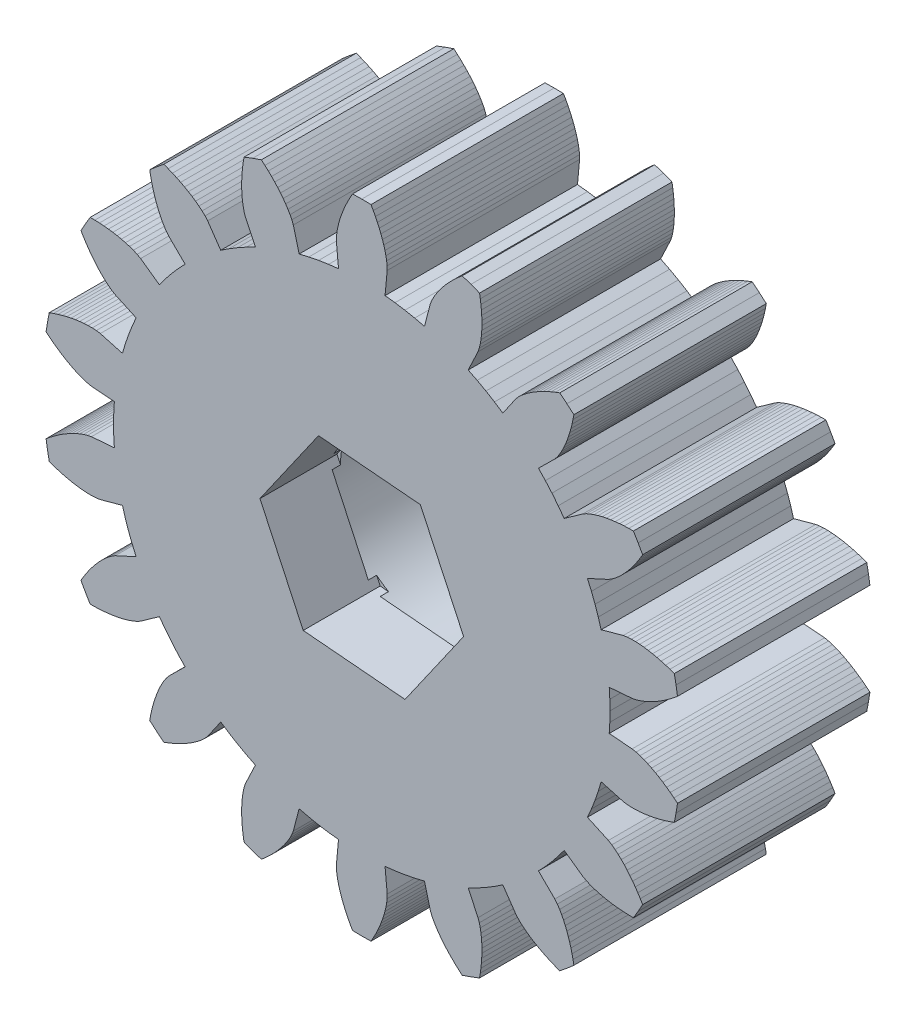
SolidWorks part; units mm, degrees
ref_plane "前视基准面" through (0, 0, 0) normal (0, 0, 1) x (1, 0, 0)
ref_plane "上视基准面" through (0, 0, 0) normal (0, 1, 0) x (1, 0, 0)
ref_plane "右视基准面" through (0, 0, 0) normal (1, 0, 0) x (0, 0, -1)
other "Configuration Table"
sketch "M1 Z18 pinion profile profile" plane through (0, 0, 0) normal (0, 0, 1) x (1, 0, 0)
  line L0 (1.344, 7.6224) -> (1.0355, 7.6704)
  line L1 (1.0355, 7.6704) -> (0.7252, 7.7059)
  line L2 (0.7252, 7.7059) -> (0.7924, 8.42)
  line L3 (0.7924, 8.42) -> (0.7898, 8.5452)
  line L4 (0.7898, 8.5452) -> (0.775, 8.6715)
  line L5 (0.775, 8.6715) -> (0.752, 8.7983)
  line L6 (0.752, 8.7983) -> (0.7221, 8.9257)
  line L7 (0.7221, 8.9257) -> (0.686, 9.0533)
  line L8 (0.686, 9.0533) -> (0.6441, 9.181)
  line L9 (0.6441, 9.181) -> (0.5969, 9.3089)
  line L10 (0.5969, 9.3089) -> (0.5446, 9.4367)
  line L11 (0.5446, 9.4367) -> (0.4873, 9.5644)
  line L12 (0.4873, 9.5644) -> (0.4253, 9.6919)
  line L13 (0.4253, 9.6919) -> (0.3586, 9.8191)
  line L14 (0.3586, 9.8191) -> (0.2874, 9.9458)
  line L15 (0.2874, 9.9458) -> (0, 9.95)
  line L16 (0, 9.95) -> (-0.2874, 9.9458)
  line L17 (-0.2874, 9.9458) -> (-0.3586, 9.8191)
  line L18 (-0.3586, 9.8191) -> (-0.4253, 9.6919)
  line L19 (-0.4253, 9.6919) -> (-0.4873, 9.5644)
  line L20 (-0.4873, 9.5644) -> (-0.5446, 9.4367)
  line L21 (-0.5446, 9.4367) -> (-0.5969, 9.3089)
  line L22 (-0.5969, 9.3089) -> (-0.6441, 9.181)
  line L23 (-0.6441, 9.181) -> (-0.686, 9.0533)
  line L24 (-0.686, 9.0533) -> (-0.7221, 8.9257)
  line L25 (-0.7221, 8.9257) -> (-0.752, 8.7983)
  line L26 (-0.752, 8.7983) -> (-0.775, 8.6715)
  line L27 (-0.775, 8.6715) -> (-0.7898, 8.5452)
  line L28 (-0.7898, 8.5452) -> (-0.7924, 8.42)
  line L29 (-0.7924, 8.42) -> (-0.7252, 7.7059)
  line L30 (-0.7252, 7.7059) -> (-1.0355, 7.6704)
  line L31 (-1.0355, 7.6704) -> (-1.344, 7.6224)
  line L32 (-1.344, 7.6224) -> (-1.6504, 7.562)
  line L33 (-1.6504, 7.562) -> (-1.9541, 7.4893)
  line L34 (-1.9541, 7.4893) -> (-2.1352, 8.1833)
  line L35 (-2.1352, 8.1833) -> (-2.1804, 8.3)
  line L36 (-2.1804, 8.3) -> (-2.2375, 8.4136)
  line L37 (-2.2375, 8.4136) -> (-2.3025, 8.5249)
  line L38 (-2.3025, 8.5249) -> (-2.3742, 8.6343)
  line L39 (-2.3742, 8.6343) -> (-2.4518, 8.7419)
  line L40 (-2.4518, 8.7419) -> (-2.5348, 8.8477)
  line L41 (-2.5348, 8.8477) -> (-2.6229, 8.9517)
  line L42 (-2.6229, 8.9517) -> (-2.7158, 9.0539)
  line L43 (-2.7158, 9.0539) -> (-2.8133, 9.1543)
  line L44 (-2.8133, 9.1543) -> (-2.9152, 9.2528)
  line L45 (-2.9152, 9.2528) -> (-3.0213, 9.3495)
  line L46 (-3.0213, 9.3495) -> (-3.1316, 9.4443)
  line L47 (-3.1316, 9.4443) -> (-3.4031, 9.3499)
  line L48 (-3.4031, 9.3499) -> (-3.6717, 9.2478)
  line L49 (-3.6717, 9.2478) -> (-3.6953, 9.1042)
  line L50 (-3.6953, 9.1042) -> (-3.7145, 8.9619)
  line L51 (-3.7145, 8.9619) -> (-3.7292, 8.8209)
  line L52 (-3.7292, 8.8209) -> (-3.7393, 8.6813)
  line L53 (-3.7393, 8.6813) -> (-3.7448, 8.5433)
  line L54 (-3.7448, 8.5433) -> (-3.7454, 8.4071)
  line L55 (-3.7454, 8.4071) -> (-3.741, 8.2727)
  line L56 (-3.741, 8.2727) -> (-3.7313, 8.1404)
  line L57 (-3.7313, 8.1404) -> (-3.7159, 8.0105)
  line L58 (-3.7159, 8.0105) -> (-3.6941, 7.8834)
  line L59 (-3.6941, 7.8834) -> (-3.6648, 7.7597)
  line L60 (-3.6648, 7.7597) -> (-3.6245, 7.6412)
  line L61 (-3.6245, 7.6412) -> (-3.3171, 6.9932)
  line L62 (-3.3171, 6.9932) -> (-3.5965, 6.8537)
  line L63 (-3.5965, 6.8537) -> (-3.87, 6.703)
  line L64 (-3.87, 6.703) -> (-4.1372, 6.5415)
  line L65 (-4.1372, 6.5415) -> (-4.3977, 6.3693)
  line L66 (-4.3977, 6.3693) -> (-4.8052, 6.9595)
  line L67 (-4.8052, 6.9595) -> (-4.8877, 7.0537)
  line L68 (-4.8877, 7.0537) -> (-4.9802, 7.1409)
  line L69 (-4.9802, 7.1409) -> (-5.0794, 7.2233)
  line L70 (-5.0794, 7.2233) -> (-5.1841, 7.3016)
  line L71 (-5.1841, 7.3016) -> (-5.2938, 7.3761)
  line L72 (-5.2938, 7.3761) -> (-5.408, 7.4471)
  line L73 (-5.408, 7.4471) -> (-5.5264, 7.5147)
  line L74 (-5.5264, 7.5147) -> (-5.6486, 7.579)
  line L75 (-5.6486, 7.579) -> (-5.7746, 7.64)
  line L76 (-5.7746, 7.64) -> (-5.904, 7.6978)
  line L77 (-5.904, 7.6978) -> (-6.0369, 7.7523)
  line L78 (-6.0369, 7.7523) -> (-6.1729, 7.8037)
  line L79 (-6.1729, 7.8037) -> (-6.3957, 7.6221)
  line L80 (-6.3957, 7.6221) -> (-6.6132, 7.4342)
  line L81 (-6.6132, 7.4342) -> (-6.5863, 7.2913)
  line L82 (-6.5863, 7.2913) -> (-6.5556, 7.151)
  line L83 (-6.5556, 7.151) -> (-6.5212, 7.0135)
  line L84 (-6.5212, 7.0135) -> (-6.483, 6.8789)
  line L85 (-6.483, 6.8789) -> (-6.4409, 6.7473)
  line L86 (-6.4409, 6.7473) -> (-6.3949, 6.619)
  line L87 (-6.3949, 6.619) -> (-6.3448, 6.4943)
  line L88 (-6.3448, 6.4943) -> (-6.2905, 6.3733)
  line L89 (-6.2905, 6.3733) -> (-6.2316, 6.2565)
  line L90 (-6.2316, 6.2565) -> (-6.1676, 6.1445)
  line L91 (-6.1676, 6.1445) -> (-6.0978, 6.0383)
  line L92 (-6.0978, 6.0383) -> (-6.0193, 5.9407)
  line L93 (-6.0193, 5.9407) -> (-5.5089, 5.4369)
  line L94 (-5.5089, 5.4369) -> (-5.7237, 5.2103)
  line L95 (-5.7237, 5.2103) -> (-5.9292, 4.9752)
  line L96 (-5.9292, 4.9752) -> (-6.125, 4.732)
  line L97 (-6.125, 4.732) -> (-6.3109, 4.481)
  line L98 (-6.3109, 4.481) -> (-6.8957, 4.8963)
  line L99 (-6.8957, 4.8963) -> (-7.0055, 4.9566)
  line L100 (-7.0055, 4.9566) -> (-7.1222, 5.0069)
  line L101 (-7.1222, 5.0069) -> (-7.2436, 5.0504)
  line L102 (-7.2436, 5.0504) -> (-7.3688, 5.0882)
  line L103 (-7.3688, 5.0882) -> (-7.4974, 5.1207)
  line L104 (-7.4974, 5.1207) -> (-7.629, 5.1484)
  line L105 (-7.629, 5.1484) -> (-7.7633, 5.1714)
  line L106 (-7.7633, 5.1714) -> (-7.9001, 5.19)
  line L107 (-7.9001, 5.19) -> (-8.0393, 5.2042)
  line L108 (-8.0393, 5.2042) -> (-8.1808, 5.2143)
  line L109 (-8.1808, 5.2143) -> (-8.3243, 5.2201)
  line L110 (-8.3243, 5.2201) -> (-8.4697, 5.2218)
  line L111 (-8.4697, 5.2218) -> (-8.617, 4.975)
  line L112 (-8.617, 4.975) -> (-8.757, 4.7241)
  line L113 (-8.757, 4.7241) -> (-8.6829, 4.599)
  line L114 (-8.6829, 4.599) -> (-8.6061, 4.4776)
  line L115 (-8.6061, 4.4776) -> (-8.5267, 4.3602)
  line L116 (-8.5267, 4.3602) -> (-8.4447, 4.2467)
  line L117 (-8.4447, 4.2467) -> (-8.3602, 4.1375)
  line L118 (-8.3602, 4.1375) -> (-8.2731, 4.0327)
  line L119 (-8.2731, 4.0327) -> (-8.1833, 3.9326)
  line L120 (-8.1833, 3.9326) -> (-8.0909, 3.8375)
  line L121 (-8.0909, 3.8375) -> (-7.9956, 3.7479)
  line L122 (-7.9956, 3.7479) -> (-7.8972, 3.6645)
  line L123 (-7.8972, 3.6645) -> (-7.7953, 3.5886)
  line L124 (-7.7953, 3.5886) -> (-7.6882, 3.5237)
  line L125 (-7.6882, 3.5237) -> (-7.0362, 3.2249)
  line L126 (-7.0362, 3.2249) -> (-7.1605, 2.9385)
  line L127 (-7.1605, 2.9385) -> (-7.2732, 2.6472)
  line L128 (-7.2732, 2.6472) -> (-7.3741, 2.3517)
  line L129 (-7.3741, 2.3517) -> (-7.4629, 2.0523)
  line L130 (-7.4629, 2.0523) -> (-8.1545, 2.2425)
  line L131 (-8.1545, 2.2425) -> (-8.2782, 2.2617)
  line L132 (-8.2782, 2.2617) -> (-8.4051, 2.2691)
  line L133 (-8.4051, 2.2691) -> (-8.5341, 2.2684)
  line L134 (-8.5341, 2.2684) -> (-8.6647, 2.261)
  line L135 (-8.6647, 2.261) -> (-8.7966, 2.2476)
  line L136 (-8.7966, 2.2476) -> (-8.9297, 2.2286)
  line L137 (-8.9297, 2.2286) -> (-9.0638, 2.2043)
  line L138 (-9.0638, 2.2043) -> (-9.1988, 2.175)
  line L139 (-9.1988, 2.175) -> (-9.3345, 2.1408)
  line L140 (-9.3345, 2.1408) -> (-9.4708, 2.1018)
  line L141 (-9.4708, 2.1018) -> (-9.6076, 2.0582)
  line L142 (-9.6076, 2.0582) -> (-9.7448, 2.0101)
  line L143 (-9.7448, 2.0101) -> (-9.7988, 1.7278)
  line L144 (-9.7988, 1.7278) -> (-9.8446, 1.4441)
  line L145 (-9.8446, 1.4441) -> (-9.7322, 1.3519)
  line L146 (-9.7322, 1.3519) -> (-9.6185, 1.2641)
  line L147 (-9.6185, 1.2641) -> (-9.5037, 1.1809)
  line L148 (-9.5037, 1.1809) -> (-9.3879, 1.1023)
  line L149 (-9.3879, 1.1023) -> (-9.2711, 1.0286)
  line L150 (-9.2711, 1.0286) -> (-9.1534, 0.9599)
  line L151 (-9.1534, 0.9599) -> (-9.0348, 0.8965)
  line L152 (-9.0348, 0.8965) -> (-8.9155, 0.8388)
  line L153 (-8.9155, 0.8388) -> (-8.7953, 0.7872)
  line L154 (-8.7953, 0.7872) -> (-8.6743, 0.7425)
  line L155 (-8.6743, 0.7425) -> (-8.5525, 0.706)
  line L156 (-8.5525, 0.706) -> (-8.4297, 0.6817)
  line L157 (-8.4297, 0.6817) -> (-7.7148, 0.6239)
  line L158 (-7.7148, 0.6239) -> (-7.7337, 0.3122)
  line L159 (-7.7337, 0.3122) -> (-7.74, 0)
  line L160 (-7.74, 0) -> (-7.7337, -0.3122)
  line L161 (-7.7337, -0.3122) -> (-7.7148, -0.6239)
  line L162 (-7.7148, -0.6239) -> (-8.4297, -0.6817)
  line L163 (-8.4297, -0.6817) -> (-8.5525, -0.706)
  line L164 (-8.5525, -0.706) -> (-8.6743, -0.7425)
  line L165 (-8.6743, -0.7425) -> (-8.7953, -0.7872)
  line L166 (-8.7953, -0.7872) -> (-8.9155, -0.8388)
  line L167 (-8.9155, -0.8388) -> (-9.0348, -0.8965)
  line L168 (-9.0348, -0.8965) -> (-9.1534, -0.9599)
  line L169 (-9.1534, -0.9599) -> (-9.2711, -1.0286)
  line L170 (-9.2711, -1.0286) -> (-9.3879, -1.1023)
  line L171 (-9.3879, -1.1023) -> (-9.5037, -1.1809)
  line L172 (-9.5037, -1.1809) -> (-9.6185, -1.2641)
  line L173 (-9.6185, -1.2641) -> (-9.7322, -1.3519)
  line L174 (-9.7322, -1.3519) -> (-9.8446, -1.4441)
  line L175 (-9.8446, -1.4441) -> (-9.7988, -1.7278)
  line L176 (-9.7988, -1.7278) -> (-9.7448, -2.0101)
  line L177 (-9.7448, -2.0101) -> (-9.6076, -2.0582)
  line L178 (-9.6076, -2.0582) -> (-9.4708, -2.1018)
  line L179 (-9.4708, -2.1018) -> (-9.3345, -2.1408)
  line L180 (-9.3345, -2.1408) -> (-9.1988, -2.175)
  line L181 (-9.1988, -2.175) -> (-9.0638, -2.2043)
  line L182 (-9.0638, -2.2043) -> (-8.9297, -2.2286)
  line L183 (-8.9297, -2.2286) -> (-8.7966, -2.2476)
  line L184 (-8.7966, -2.2476) -> (-8.6647, -2.261)
  line L185 (-8.6647, -2.261) -> (-8.5341, -2.2684)
  line L186 (-8.5341, -2.2684) -> (-8.4051, -2.2691)
  line L187 (-8.4051, -2.2691) -> (-8.2782, -2.2617)
  line L188 (-8.2782, -2.2617) -> (-8.1545, -2.2425)
  line L189 (-8.1545, -2.2425) -> (-7.4629, -2.0523)
  line L190 (-7.4629, -2.0523) -> (-7.3741, -2.3517)
  line L191 (-7.3741, -2.3517) -> (-7.2732, -2.6472)
  line L192 (-7.2732, -2.6472) -> (-7.1605, -2.9385)
  line L193 (-7.1605, -2.9385) -> (-7.0362, -3.2249)
  line L194 (-7.0362, -3.2249) -> (-7.6882, -3.5237)
  line L195 (-7.6882, -3.5237) -> (-7.7953, -3.5886)
  line L196 (-7.7953, -3.5886) -> (-7.8972, -3.6645)
  line L197 (-7.8972, -3.6645) -> (-7.9956, -3.7479)
  line L198 (-7.9956, -3.7479) -> (-8.0909, -3.8375)
  line L199 (-8.0909, -3.8375) -> (-8.1833, -3.9326)
  line L200 (-8.1833, -3.9326) -> (-8.2731, -4.0327)
  line L201 (-8.2731, -4.0327) -> (-8.3602, -4.1375)
  line L202 (-8.3602, -4.1375) -> (-8.4447, -4.2467)
  line L203 (-8.4447, -4.2467) -> (-8.5267, -4.3602)
  line L204 (-8.5267, -4.3602) -> (-8.6061, -4.4776)
  line L205 (-8.6061, -4.4776) -> (-8.6829, -4.599)
  line L206 (-8.6829, -4.599) -> (-8.757, -4.7241)
  line L207 (-8.757, -4.7241) -> (-8.617, -4.975)
  line L208 (-8.617, -4.975) -> (-8.4697, -5.2218)
  line L209 (-8.4697, -5.2218) -> (-8.3243, -5.2201)
  line L210 (-8.3243, -5.2201) -> (-8.1808, -5.2143)
  line L211 (-8.1808, -5.2143) -> (-8.0393, -5.2042)
  line L212 (-8.0393, -5.2042) -> (-7.9001, -5.19)
  line L213 (-7.9001, -5.19) -> (-7.7633, -5.1714)
  line L214 (-7.7633, -5.1714) -> (-7.629, -5.1484)
  line L215 (-7.629, -5.1484) -> (-7.4974, -5.1207)
  line L216 (-7.4974, -5.1207) -> (-7.3688, -5.0882)
  line L217 (-7.3688, -5.0882) -> (-7.2436, -5.0504)
  line L218 (-7.2436, -5.0504) -> (-7.1222, -5.0069)
  line L219 (-7.1222, -5.0069) -> (-7.0055, -4.9566)
  line L220 (-7.0055, -4.9566) -> (-6.8957, -4.8963)
  line L221 (-6.8957, -4.8963) -> (-6.3109, -4.481)
  line L222 (-6.3109, -4.481) -> (-6.125, -4.732)
  line L223 (-6.125, -4.732) -> (-5.9292, -4.9752)
  line L224 (-5.9292, -4.9752) -> (-5.7237, -5.2103)
  line L225 (-5.7237, -5.2103) -> (-5.5089, -5.4369)
  line L226 (-5.5089, -5.4369) -> (-6.0193, -5.9407)
  line L227 (-6.0193, -5.9407) -> (-6.0978, -6.0383)
  line L228 (-6.0978, -6.0383) -> (-6.1676, -6.1445)
  line L229 (-6.1676, -6.1445) -> (-6.2316, -6.2565)
  line L230 (-6.2316, -6.2565) -> (-6.2905, -6.3733)
  line L231 (-6.2905, -6.3733) -> (-6.3448, -6.4943)
  line L232 (-6.3448, -6.4943) -> (-6.3949, -6.619)
  line L233 (-6.3949, -6.619) -> (-6.4409, -6.7473)
  line L234 (-6.4409, -6.7473) -> (-6.483, -6.8789)
  line L235 (-6.483, -6.8789) -> (-6.5212, -7.0135)
  line L236 (-6.5212, -7.0135) -> (-6.5556, -7.151)
  line L237 (-6.5556, -7.151) -> (-6.5863, -7.2913)
  line L238 (-6.5863, -7.2913) -> (-6.6132, -7.4342)
  line L239 (-6.6132, -7.4342) -> (-6.3957, -7.6221)
  line L240 (-6.3957, -7.6221) -> (-6.1729, -7.8037)
  line L241 (-6.1729, -7.8037) -> (-6.0369, -7.7523)
  line L242 (-6.0369, -7.7523) -> (-5.904, -7.6978)
  line L243 (-5.904, -7.6978) -> (-5.7746, -7.64)
  line L244 (-5.7746, -7.64) -> (-5.6486, -7.579)
  line L245 (-5.6486, -7.579) -> (-5.5264, -7.5147)
  line L246 (-5.5264, -7.5147) -> (-5.408, -7.4471)
  line L247 (-5.408, -7.4471) -> (-5.2938, -7.3761)
  line L248 (-5.2938, -7.3761) -> (-5.1841, -7.3016)
  line L249 (-5.1841, -7.3016) -> (-5.0794, -7.2233)
  line L250 (-5.0794, -7.2233) -> (-4.9802, -7.1409)
  line L251 (-4.9802, -7.1409) -> (-4.8877, -7.0537)
  line L252 (-4.8877, -7.0537) -> (-4.8052, -6.9595)
  line L253 (-4.8052, -6.9595) -> (-4.3977, -6.3693)
  line L254 (-4.3977, -6.3693) -> (-4.1372, -6.5415)
  line L255 (-4.1372, -6.5415) -> (-3.87, -6.703)
  line L256 (-3.87, -6.703) -> (-3.5965, -6.8537)
  line L257 (-3.5965, -6.8537) -> (-3.3171, -6.9932)
  line L258 (-3.3171, -6.9932) -> (-3.6245, -7.6412)
  line L259 (-3.6245, -7.6412) -> (-3.6648, -7.7597)
  line L260 (-3.6648, -7.7597) -> (-3.6941, -7.8834)
  line L261 (-3.6941, -7.8834) -> (-3.7159, -8.0105)
  line L262 (-3.7159, -8.0105) -> (-3.7313, -8.1404)
  line L263 (-3.7313, -8.1404) -> (-3.741, -8.2727)
  line L264 (-3.741, -8.2727) -> (-3.7454, -8.4071)
  line L265 (-3.7454, -8.4071) -> (-3.7448, -8.5433)
  line L266 (-3.7448, -8.5433) -> (-3.7393, -8.6813)
  line L267 (-3.7393, -8.6813) -> (-3.7292, -8.8209)
  line L268 (-3.7292, -8.8209) -> (-3.7145, -8.9619)
  line L269 (-3.7145, -8.9619) -> (-3.6953, -9.1042)
  line L270 (-3.6953, -9.1042) -> (-3.6717, -9.2478)
  line L271 (-3.6717, -9.2478) -> (-3.4031, -9.3499)
  line L272 (-3.4031, -9.3499) -> (-3.1316, -9.4443)
  line L273 (-3.1316, -9.4443) -> (-3.0213, -9.3495)
  line L274 (-3.0213, -9.3495) -> (-2.9152, -9.2528)
  line L275 (-2.9152, -9.2528) -> (-2.8133, -9.1543)
  line L276 (-2.8133, -9.1543) -> (-2.7158, -9.0539)
  line L277 (-2.7158, -9.0539) -> (-2.6229, -8.9517)
  line L278 (-2.6229, -8.9517) -> (-2.5348, -8.8477)
  line L279 (-2.5348, -8.8477) -> (-2.4518, -8.7419)
  line L280 (-2.4518, -8.7419) -> (-2.3742, -8.6343)
  line L281 (-2.3742, -8.6343) -> (-2.3025, -8.5249)
  line L282 (-2.3025, -8.5249) -> (-2.2375, -8.4136)
  line L283 (-2.2375, -8.4136) -> (-2.1804, -8.3)
  line L284 (-2.1804, -8.3) -> (-2.1352, -8.1833)
  line L285 (-2.1352, -8.1833) -> (-1.9541, -7.4893)
  line L286 (-1.9541, -7.4893) -> (-1.6504, -7.562)
  line L287 (-1.6504, -7.562) -> (-1.344, -7.6224)
  line L288 (-1.344, -7.6224) -> (-1.0355, -7.6704)
  line L289 (-1.0355, -7.6704) -> (-0.7252, -7.7059)
  line L290 (-0.7252, -7.7059) -> (-0.7924, -8.42)
  line L291 (-0.7924, -8.42) -> (-0.7898, -8.5452)
  line L292 (-0.7898, -8.5452) -> (-0.775, -8.6715)
  line L293 (-0.775, -8.6715) -> (-0.752, -8.7983)
  line L294 (-0.752, -8.7983) -> (-0.7221, -8.9257)
  line L295 (-0.7221, -8.9257) -> (-0.686, -9.0533)
  line L296 (-0.686, -9.0533) -> (-0.6441, -9.181)
  line L297 (-0.6441, -9.181) -> (-0.5969, -9.3089)
  line L298 (-0.5969, -9.3089) -> (-0.5446, -9.4367)
  line L299 (-0.5446, -9.4367) -> (-0.4873, -9.5644)
  line L300 (-0.4873, -9.5644) -> (-0.4253, -9.6919)
  line L301 (-0.4253, -9.6919) -> (-0.3586, -9.8191)
  line L302 (-0.3586, -9.8191) -> (-0.2874, -9.9458)
  line L303 (-0.2874, -9.9458) -> (0, -9.95)
  line L304 (0, -9.95) -> (0.2874, -9.9458)
  line L305 (0.2874, -9.9458) -> (0.3586, -9.8191)
  line L306 (0.3586, -9.8191) -> (0.4253, -9.6919)
  line L307 (0.4253, -9.6919) -> (0.4873, -9.5644)
  line L308 (0.4873, -9.5644) -> (0.5446, -9.4367)
  line L309 (0.5446, -9.4367) -> (0.5969, -9.3089)
  line L310 (0.5969, -9.3089) -> (0.6441, -9.181)
  line L311 (0.6441, -9.181) -> (0.686, -9.0533)
  line L312 (0.686, -9.0533) -> (0.7221, -8.9257)
  line L313 (0.7221, -8.9257) -> (0.752, -8.7983)
  line L314 (0.752, -8.7983) -> (0.775, -8.6715)
  line L315 (0.775, -8.6715) -> (0.7898, -8.5452)
  line L316 (0.7898, -8.5452) -> (0.7924, -8.42)
  line L317 (0.7924, -8.42) -> (0.7252, -7.7059)
  line L318 (0.7252, -7.7059) -> (1.0355, -7.6704)
  line L319 (1.0355, -7.6704) -> (1.344, -7.6224)
  line L320 (1.344, -7.6224) -> (1.6504, -7.562)
  line L321 (1.6504, -7.562) -> (1.9541, -7.4893)
  line L322 (1.9541, -7.4893) -> (2.1352, -8.1833)
  line L323 (2.1352, -8.1833) -> (2.1804, -8.3)
  line L324 (2.1804, -8.3) -> (2.2375, -8.4136)
  line L325 (2.2375, -8.4136) -> (2.3025, -8.5249)
  line L326 (2.3025, -8.5249) -> (2.3742, -8.6343)
  line L327 (2.3742, -8.6343) -> (2.4518, -8.7419)
  line L328 (2.4518, -8.7419) -> (2.5348, -8.8477)
  line L329 (2.5348, -8.8477) -> (2.6229, -8.9517)
  line L330 (2.6229, -8.9517) -> (2.7158, -9.0539)
  line L331 (2.7158, -9.0539) -> (2.8133, -9.1543)
  line L332 (2.8133, -9.1543) -> (2.9152, -9.2528)
  line L333 (2.9152, -9.2528) -> (3.0213, -9.3495)
  line L334 (3.0213, -9.3495) -> (3.1316, -9.4443)
  line L335 (3.1316, -9.4443) -> (3.4031, -9.3499)
  line L336 (3.4031, -9.3499) -> (3.6717, -9.2478)
  line L337 (3.6717, -9.2478) -> (3.6953, -9.1042)
  line L338 (3.6953, -9.1042) -> (3.7145, -8.9619)
  line L339 (3.7145, -8.9619) -> (3.7292, -8.8209)
  line L340 (3.7292, -8.8209) -> (3.7393, -8.6813)
  line L341 (3.7393, -8.6813) -> (3.7448, -8.5433)
  line L342 (3.7448, -8.5433) -> (3.7454, -8.4071)
  line L343 (3.7454, -8.4071) -> (3.741, -8.2727)
  line L344 (3.741, -8.2727) -> (3.7313, -8.1404)
  line L345 (3.7313, -8.1404) -> (3.7159, -8.0105)
  line L346 (3.7159, -8.0105) -> (3.6941, -7.8834)
  line L347 (3.6941, -7.8834) -> (3.6648, -7.7597)
  line L348 (3.6648, -7.7597) -> (3.6245, -7.6412)
  line L349 (3.6245, -7.6412) -> (3.3171, -6.9932)
  line L350 (3.3171, -6.9932) -> (3.5965, -6.8537)
  line L351 (3.5965, -6.8537) -> (3.87, -6.703)
  line L352 (3.87, -6.703) -> (4.1372, -6.5415)
  line L353 (4.1372, -6.5415) -> (4.3977, -6.3693)
  line L354 (4.3977, -6.3693) -> (4.8052, -6.9595)
  line L355 (4.8052, -6.9595) -> (4.8877, -7.0537)
  line L356 (4.8877, -7.0537) -> (4.9802, -7.1409)
  line L357 (4.9802, -7.1409) -> (5.0794, -7.2233)
  line L358 (5.0794, -7.2233) -> (5.1841, -7.3016)
  line L359 (5.1841, -7.3016) -> (5.2938, -7.3761)
  line L360 (5.2938, -7.3761) -> (5.408, -7.4471)
  line L361 (5.408, -7.4471) -> (5.5264, -7.5147)
  line L362 (5.5264, -7.5147) -> (5.6486, -7.579)
  line L363 (5.6486, -7.579) -> (5.7746, -7.64)
  line L364 (5.7746, -7.64) -> (5.904, -7.6978)
  line L365 (5.904, -7.6978) -> (6.0369, -7.7523)
  line L366 (6.0369, -7.7523) -> (6.1729, -7.8037)
  line L367 (6.1729, -7.8037) -> (6.3957, -7.6221)
  line L368 (6.3957, -7.6221) -> (6.6132, -7.4342)
  line L369 (6.6132, -7.4342) -> (6.5863, -7.2913)
  line L370 (6.5863, -7.2913) -> (6.5556, -7.151)
  line L371 (6.5556, -7.151) -> (6.5212, -7.0135)
  line L372 (6.5212, -7.0135) -> (6.483, -6.8789)
  line L373 (6.483, -6.8789) -> (6.4409, -6.7473)
  line L374 (6.4409, -6.7473) -> (6.3949, -6.619)
  line L375 (6.3949, -6.619) -> (6.3448, -6.4943)
  line L376 (6.3448, -6.4943) -> (6.2905, -6.3733)
  line L377 (6.2905, -6.3733) -> (6.2316, -6.2565)
  line L378 (6.2316, -6.2565) -> (6.1676, -6.1445)
  line L379 (6.1676, -6.1445) -> (6.0978, -6.0383)
  line L380 (6.0978, -6.0383) -> (6.0193, -5.9407)
  line L381 (6.0193, -5.9407) -> (5.5089, -5.4369)
  line L382 (5.5089, -5.4369) -> (5.7237, -5.2103)
  line L383 (5.7237, -5.2103) -> (5.9292, -4.9752)
  line L384 (5.9292, -4.9752) -> (6.125, -4.732)
  line L385 (6.125, -4.732) -> (6.3109, -4.481)
  line L386 (6.3109, -4.481) -> (6.8957, -4.8963)
  line L387 (6.8957, -4.8963) -> (7.0055, -4.9566)
  line L388 (7.0055, -4.9566) -> (7.1222, -5.0069)
  line L389 (7.1222, -5.0069) -> (7.2436, -5.0504)
  line L390 (7.2436, -5.0504) -> (7.3688, -5.0882)
  line L391 (7.3688, -5.0882) -> (7.4974, -5.1207)
  line L392 (7.4974, -5.1207) -> (7.629, -5.1484)
  line L393 (7.629, -5.1484) -> (7.7633, -5.1714)
  line L394 (7.7633, -5.1714) -> (7.9001, -5.19)
  line L395 (7.9001, -5.19) -> (8.0393, -5.2042)
  line L396 (8.0393, -5.2042) -> (8.1808, -5.2143)
  line L397 (8.1808, -5.2143) -> (8.3243, -5.2201)
  line L398 (8.3243, -5.2201) -> (8.4697, -5.2218)
  line L399 (8.4697, -5.2218) -> (8.617, -4.975)
  line L400 (8.617, -4.975) -> (8.757, -4.7241)
  line L401 (8.757, -4.7241) -> (8.6829, -4.599)
  line L402 (8.6829, -4.599) -> (8.6061, -4.4776)
  line L403 (8.6061, -4.4776) -> (8.5267, -4.3602)
  line L404 (8.5267, -4.3602) -> (8.4447, -4.2467)
  line L405 (8.4447, -4.2467) -> (8.3602, -4.1375)
  line L406 (8.3602, -4.1375) -> (8.2731, -4.0327)
  line L407 (8.2731, -4.0327) -> (8.1833, -3.9326)
  line L408 (8.1833, -3.9326) -> (8.0909, -3.8375)
  line L409 (8.0909, -3.8375) -> (7.9956, -3.7479)
  line L410 (7.9956, -3.7479) -> (7.8972, -3.6645)
  line L411 (7.8972, -3.6645) -> (7.7953, -3.5886)
  line L412 (7.7953, -3.5886) -> (7.6882, -3.5237)
  line L413 (7.6882, -3.5237) -> (7.0362, -3.2249)
  line L414 (7.0362, -3.2249) -> (7.1605, -2.9385)
  line L415 (7.1605, -2.9385) -> (7.2732, -2.6472)
  line L416 (7.2732, -2.6472) -> (7.3741, -2.3517)
  line L417 (7.3741, -2.3517) -> (7.4629, -2.0523)
  line L418 (7.4629, -2.0523) -> (8.1545, -2.2425)
  line L419 (8.1545, -2.2425) -> (8.2782, -2.2617)
  line L420 (8.2782, -2.2617) -> (8.4051, -2.2691)
  line L421 (8.4051, -2.2691) -> (8.5341, -2.2684)
  line L422 (8.5341, -2.2684) -> (8.6647, -2.261)
  line L423 (8.6647, -2.261) -> (8.7966, -2.2476)
  line L424 (8.7966, -2.2476) -> (8.9297, -2.2286)
  line L425 (8.9297, -2.2286) -> (9.0638, -2.2043)
  line L426 (9.0638, -2.2043) -> (9.1988, -2.175)
  line L427 (9.1988, -2.175) -> (9.3345, -2.1408)
  line L428 (9.3345, -2.1408) -> (9.4708, -2.1018)
  line L429 (9.4708, -2.1018) -> (9.6076, -2.0582)
  line L430 (9.6076, -2.0582) -> (9.7448, -2.0101)
  line L431 (9.7448, -2.0101) -> (9.7988, -1.7278)
  line L432 (9.7988, -1.7278) -> (9.8446, -1.4441)
  line L433 (9.8446, -1.4441) -> (9.7322, -1.3519)
  line L434 (9.7322, -1.3519) -> (9.6185, -1.2641)
  line L435 (9.6185, -1.2641) -> (9.5037, -1.1809)
  line L436 (9.5037, -1.1809) -> (9.3879, -1.1023)
  line L437 (9.3879, -1.1023) -> (9.2711, -1.0286)
  line L438 (9.2711, -1.0286) -> (9.1534, -0.9599)
  line L439 (9.1534, -0.9599) -> (9.0348, -0.8965)
  line L440 (9.0348, -0.8965) -> (8.9155, -0.8388)
  line L441 (8.9155, -0.8388) -> (8.7953, -0.7872)
  line L442 (8.7953, -0.7872) -> (8.6743, -0.7425)
  line L443 (8.6743, -0.7425) -> (8.5525, -0.706)
  line L444 (8.5525, -0.706) -> (8.4297, -0.6817)
  line L445 (8.4297, -0.6817) -> (7.7148, -0.6239)
  line L446 (7.7148, -0.6239) -> (7.7337, -0.3122)
  line L447 (7.7337, -0.3122) -> (7.74, 0)
  line L448 (7.74, 0) -> (7.7337, 0.3122)
  line L449 (7.7337, 0.3122) -> (7.7148, 0.6239)
  line L450 (7.7148, 0.6239) -> (8.4297, 0.6817)
  line L451 (8.4297, 0.6817) -> (8.5525, 0.706)
  line L452 (8.5525, 0.706) -> (8.6743, 0.7425)
  line L453 (8.6743, 0.7425) -> (8.7953, 0.7872)
  line L454 (8.7953, 0.7872) -> (8.9155, 0.8388)
  line L455 (8.9155, 0.8388) -> (9.0348, 0.8965)
  line L456 (9.0348, 0.8965) -> (9.1534, 0.9599)
  line L457 (9.1534, 0.9599) -> (9.2711, 1.0286)
  line L458 (9.2711, 1.0286) -> (9.3879, 1.1023)
  line L459 (9.3879, 1.1023) -> (9.5037, 1.1809)
  line L460 (9.5037, 1.1809) -> (9.6185, 1.2641)
  line L461 (9.6185, 1.2641) -> (9.7322, 1.3519)
  line L462 (9.7322, 1.3519) -> (9.8446, 1.4441)
  line L463 (9.8446, 1.4441) -> (9.7988, 1.7278)
  line L464 (9.7988, 1.7278) -> (9.7448, 2.0101)
  line L465 (9.7448, 2.0101) -> (9.6076, 2.0582)
  line L466 (9.6076, 2.0582) -> (9.4708, 2.1018)
  line L467 (9.4708, 2.1018) -> (9.3345, 2.1408)
  line L468 (9.3345, 2.1408) -> (9.1988, 2.175)
  line L469 (9.1988, 2.175) -> (9.0638, 2.2043)
  line L470 (9.0638, 2.2043) -> (8.9297, 2.2286)
  line L471 (8.9297, 2.2286) -> (8.7966, 2.2476)
  line L472 (8.7966, 2.2476) -> (8.6647, 2.261)
  line L473 (8.6647, 2.261) -> (8.5341, 2.2684)
  line L474 (8.5341, 2.2684) -> (8.4051, 2.2691)
  line L475 (8.4051, 2.2691) -> (8.2782, 2.2617)
  line L476 (8.2782, 2.2617) -> (8.1545, 2.2425)
  line L477 (8.1545, 2.2425) -> (7.4629, 2.0523)
  line L478 (7.4629, 2.0523) -> (7.3741, 2.3517)
  line L479 (7.3741, 2.3517) -> (7.2732, 2.6472)
  line L480 (7.2732, 2.6472) -> (7.1605, 2.9385)
  line L481 (7.1605, 2.9385) -> (7.0362, 3.2249)
  line L482 (7.0362, 3.2249) -> (7.6882, 3.5237)
  line L483 (7.6882, 3.5237) -> (7.7953, 3.5886)
  line L484 (7.7953, 3.5886) -> (7.8972, 3.6645)
  line L485 (7.8972, 3.6645) -> (7.9956, 3.7479)
  line L486 (7.9956, 3.7479) -> (8.0909, 3.8375)
  line L487 (8.0909, 3.8375) -> (8.1833, 3.9326)
  line L488 (8.1833, 3.9326) -> (8.2731, 4.0327)
  line L489 (8.2731, 4.0327) -> (8.3602, 4.1375)
  line L490 (8.3602, 4.1375) -> (8.4447, 4.2467)
  line L491 (8.4447, 4.2467) -> (8.5267, 4.3602)
  line L492 (8.5267, 4.3602) -> (8.6061, 4.4776)
  line L493 (8.6061, 4.4776) -> (8.6829, 4.599)
  line L494 (8.6829, 4.599) -> (8.757, 4.7241)
  line L495 (8.757, 4.7241) -> (8.617, 4.975)
  line L496 (8.617, 4.975) -> (8.4697, 5.2218)
  line L497 (8.4697, 5.2218) -> (8.3243, 5.2201)
  line L498 (8.3243, 5.2201) -> (8.1808, 5.2143)
  line L499 (8.1808, 5.2143) -> (8.0393, 5.2042)
  line L500 (8.0393, 5.2042) -> (7.9001, 5.19)
  line L501 (7.9001, 5.19) -> (7.7633, 5.1714)
  line L502 (7.7633, 5.1714) -> (7.629, 5.1484)
  line L503 (7.629, 5.1484) -> (7.4974, 5.1207)
  line L504 (7.4974, 5.1207) -> (7.3688, 5.0882)
  line L505 (7.3688, 5.0882) -> (7.2436, 5.0504)
  line L506 (7.2436, 5.0504) -> (7.1222, 5.0069)
  line L507 (7.1222, 5.0069) -> (7.0055, 4.9566)
  line L508 (7.0055, 4.9566) -> (6.8957, 4.8963)
  line L509 (6.8957, 4.8963) -> (6.3109, 4.481)
  line L510 (6.3109, 4.481) -> (6.125, 4.732)
  line L511 (6.125, 4.732) -> (5.9292, 4.9752)
  line L512 (5.9292, 4.9752) -> (5.7237, 5.2103)
  line L513 (5.7237, 5.2103) -> (5.5089, 5.4369)
  line L514 (5.5089, 5.4369) -> (6.0193, 5.9407)
  line L515 (6.0193, 5.9407) -> (6.0978, 6.0383)
  line L516 (6.0978, 6.0383) -> (6.1676, 6.1445)
  line L517 (6.1676, 6.1445) -> (6.2316, 6.2565)
  line L518 (6.2316, 6.2565) -> (6.2905, 6.3733)
  line L519 (6.2905, 6.3733) -> (6.3448, 6.4943)
  line L520 (6.3448, 6.4943) -> (6.3949, 6.619)
  line L521 (6.3949, 6.619) -> (6.4409, 6.7473)
  line L522 (6.4409, 6.7473) -> (6.483, 6.8789)
  line L523 (6.483, 6.8789) -> (6.5212, 7.0135)
  line L524 (6.5212, 7.0135) -> (6.5556, 7.151)
  line L525 (6.5556, 7.151) -> (6.5863, 7.2913)
  line L526 (6.5863, 7.2913) -> (6.6132, 7.4342)
  line L527 (6.6132, 7.4342) -> (6.3957, 7.6221)
  line L528 (6.3957, 7.6221) -> (6.1729, 7.8037)
  line L529 (6.1729, 7.8037) -> (6.0369, 7.7523)
  line L530 (6.0369, 7.7523) -> (5.904, 7.6978)
  line L531 (5.904, 7.6978) -> (5.7746, 7.64)
  line L532 (5.7746, 7.64) -> (5.6486, 7.579)
  line L533 (5.6486, 7.579) -> (5.5264, 7.5147)
  line L534 (5.5264, 7.5147) -> (5.408, 7.4471)
  line L535 (5.408, 7.4471) -> (5.2938, 7.3761)
  line L536 (5.2938, 7.3761) -> (5.1841, 7.3016)
  line L537 (5.1841, 7.3016) -> (5.0794, 7.2233)
  line L538 (5.0794, 7.2233) -> (4.9802, 7.1409)
  line L539 (4.9802, 7.1409) -> (4.8877, 7.0537)
  line L540 (4.8877, 7.0537) -> (4.8052, 6.9595)
  line L541 (4.8052, 6.9595) -> (4.3977, 6.3693)
  line L542 (4.3977, 6.3693) -> (4.1372, 6.5415)
  line L543 (4.1372, 6.5415) -> (3.87, 6.703)
  line L544 (3.87, 6.703) -> (3.5965, 6.8537)
  line L545 (3.5965, 6.8537) -> (3.3171, 6.9932)
  line L546 (3.3171, 6.9932) -> (3.6245, 7.6412)
  line L547 (3.6245, 7.6412) -> (3.6648, 7.7597)
  line L548 (3.6648, 7.7597) -> (3.6941, 7.8834)
  line L549 (3.6941, 7.8834) -> (3.7159, 8.0105)
  line L550 (3.7159, 8.0105) -> (3.7313, 8.1404)
  line L551 (3.7313, 8.1404) -> (3.741, 8.2727)
  line L552 (3.741, 8.2727) -> (3.7454, 8.4071)
  line L553 (3.7454, 8.4071) -> (3.7448, 8.5433)
  line L554 (3.7448, 8.5433) -> (3.7393, 8.6813)
  line L555 (3.7393, 8.6813) -> (3.7292, 8.8209)
  line L556 (3.7292, 8.8209) -> (3.7145, 8.9619)
  line L557 (3.7145, 8.9619) -> (3.6953, 9.1042)
  line L558 (3.6953, 9.1042) -> (3.6717, 9.2478)
  line L559 (3.6717, 9.2478) -> (3.4031, 9.3499)
  line L560 (3.4031, 9.3499) -> (3.1316, 9.4443)
  line L561 (3.1316, 9.4443) -> (3.0213, 9.3495)
  line L562 (3.0213, 9.3495) -> (2.9152, 9.2528)
  line L563 (2.9152, 9.2528) -> (2.8133, 9.1543)
  line L564 (2.8133, 9.1543) -> (2.7158, 9.0539)
  line L565 (2.7158, 9.0539) -> (2.6229, 8.9517)
  line L566 (2.6229, 8.9517) -> (2.5348, 8.8477)
  line L567 (2.5348, 8.8477) -> (2.4518, 8.7419)
  line L568 (2.4518, 8.7419) -> (2.3742, 8.6343)
  line L569 (2.3742, 8.6343) -> (2.3025, 8.5249)
  line L570 (2.3025, 8.5249) -> (2.2375, 8.4136)
  line L571 (2.2375, 8.4136) -> (2.1804, 8.3)
  line L572 (2.1804, 8.3) -> (2.1352, 8.1833)
  line L573 (2.1352, 8.1833) -> (1.9541, 7.4893)
  line L574 (1.9541, 7.4893) -> (1.6504, 7.562)
  line L575 (1.6504, 7.562) -> (1.344, 7.6224)
extrude "M1 Z18 pinion profile" add sketch "M1 Z18 pinion profile profile" along normal blind 6 from offset 40.4
sketch "Servo shaft socket profile" plane through (0, 0, 0) normal (0, 0, 1) x (1, 0, 0)
  circle A0 centre (0, 0) radius 3.065
extrude "Servo shaft socket" cut sketch "Servo shaft socket profile" along normal blind 3.96 from offset 40.3
sketch "Retaining screw bore profile" plane through (0, 0, 46.4) normal (0, 0, 1) x (1, 0, 0)
  line L1 (1.8264, 2.6117) -> (-1.3486, 2.8876)
  line L2 (-1.3486, 2.8876) -> (-3.175, 0.2758)
  line L3 (-3.175, 0.2758) -> (-1.8264, -2.6117)
  line L4 (-1.8264, -2.6117) -> (1.3486, -2.8876)
  line L5 (1.3486, -2.8876) -> (3.175, -0.2758)
  line L6 (3.175, -0.2758) -> (1.8264, 2.6117)
  circle A2 centre (0, 0) radius 2.76 construction
  dimension "D1" = 5.52
extrude "切除-拉伸2" cut sketch "Retaining screw bore profile" against normal blind 2.4
